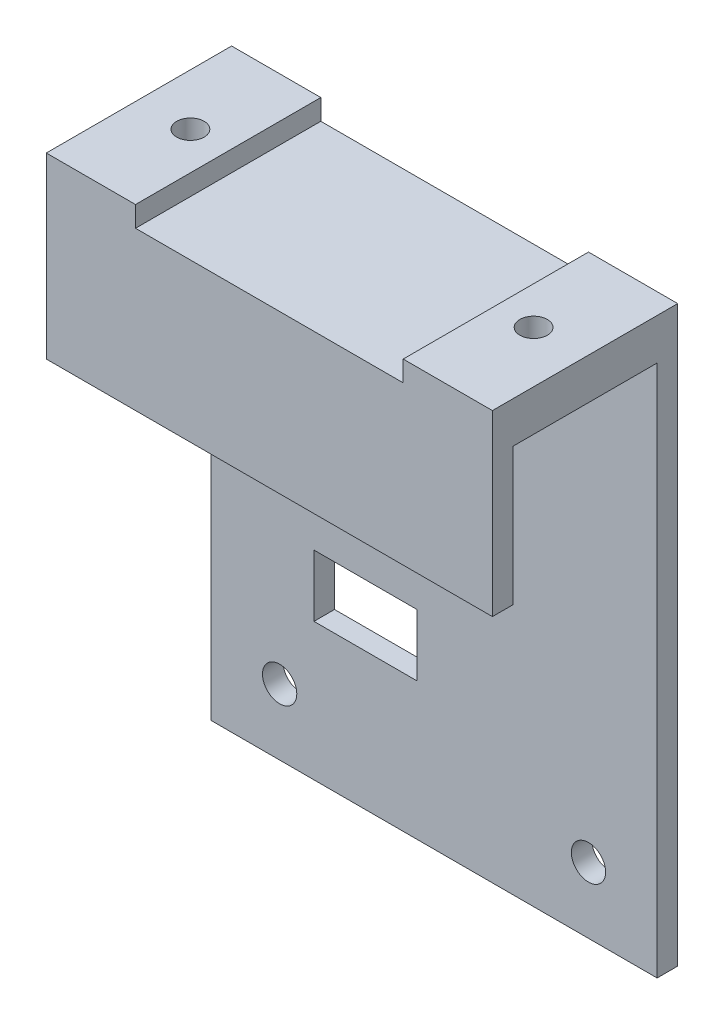
SolidWorks part; units mm, degrees
ref_plane "前视基准面" through (0, 0, 0) normal (0, 0, 1) x (1, 0, 0)
ref_plane "上视基准面" through (0, 0, 0) normal (0, 1, 0) x (1, 0, 0)
ref_plane "右视基准面" through (0, 0, 0) normal (1, 0, 0) x (0, 0, -1)
sketch "草图1" plane through (0, 0, 0) normal (0, 0, 1) x (1, 0, 0)
  line L1 (-32.5, -35) -> (32.5, -35)
  line L2 (-32.5, -35) -> (-32.5, 35)
  line L3 (-32.5, 35) -> (32.5, 35)
  line L4 (32.5, -35) -> (32.5, 35)
  line L5 (-32.5, -35) -> (32.5, 35) construction
  line L6 (-32.5, 35) -> (32.5, -35) construction
  point P0 (0, 0)
  dimension "D1" = 70
  dimension "D2" = 65
extrude "凸台-拉伸1" add sketch "草图1" along normal blind 3
sketch "草图2" plane through (0, 0, 3) normal (0, 0, 1) x (1, 0, 0)
  line L0 (32.5, -35) -> (32.5, 35) construction
  line L1 (-32.5, 35) -> (32.5, 35)
  line L2 (-32.5, 35) -> (-32.5, 29)
  line L3 (-32.5, 29) -> (32.5, 29)
  line L4 (32.5, 35) -> (32.5, 29)
  dimension "D1" = 6
extrude "凸台-拉伸2" add sketch "草图2" along normal blind 21
sketch "草图3" plane through (0, 35, 0) normal (0, 1, 0) x (1, 0, 0)
  line L1 (-32.5, -24) -> (32.5, -24)
  line L2 (-32.5, -24) -> (-32.5, -27)
  line L3 (-32.5, -27) -> (32.5, -27)
  line L4 (32.5, -24) -> (32.5, -27)
  dimension "D1" = 3
extrude "凸台-拉伸3" add sketch "草图3" against normal blind 26
sketch "草图4" plane through (0, 0, 27) normal (0, 0, 1) x (1, 0, 0)
  line L0 (-32.5, 35) -> (32.5, 35) construction
  line L1 (-19.5, 35) -> (19.5, 35)
  line L2 (-19.5, 35) -> (-19.5, 32)
  line L3 (-19.5, 32) -> (19.5, 32)
  line L4 (19.5, 35) -> (19.5, 32)
  line L5 (-32.5, 9) -> (-32.5, 35) construction
  line L6 (32.5, 9) -> (32.5, 35) construction
  dimension "D1" = 13
  dimension "D2" = 13
  dimension "D3" = 3
extrude "切除-拉伸1" cut sketch "草图4" against normal through all
sketch "草图5" plane through (0, 35, 0) normal (0, 1, 0) x (1, 0, 0)
  line L0 (0, 0) -> (25, 0)
  line L1 (32.5, 0) -> (19.5, 0) construction
  line L2 (0, 0) -> (-25, 0)
  line L3 (-19.5, 0) -> (-32.5, 0) construction
  line L4 (-25, 0) -> (-25, -13.5)
  line L7 (25, 0) -> (25, -13.5)
  circle A0 centre (-25, -13.5) radius 2
  circle A1 centre (25, -13.5) radius 2
  dimension "D5" = 4
  dimension "D6" = 4
  dimension "D1" = 25
  dimension "D2" = 25
  dimension "D3" = 13.5
  dimension "D4" = 13.5
extrude "切除-拉伸2" cut sketch "草图5" against normal through all contours A0 | A1
sketch "草图6" plane through (0, -35, 0) normal (0, -1, 0) x (1, 0, 0)
  line L4 (-32.5, 0) -> (32.5, 0)
  line L5 (32.5, 0) -> (32.5, 3)
  line L6 (32.5, 3) -> (-32.5, 3)
  line L7 (-32.5, 3) -> (-32.5, 0)
  line L8 (-32.5, 0) -> (32.5, 0)
  line L9 (32.5, 0) -> (32.5, 3)
  line L10 (32.5, 3) -> (-32.5, 3)
  line L11 (-32.5, 3) -> (-32.5, 0)
  dimension "D1" = 0
extrude "凸台-拉伸4" add sketch "草图6" along normal blind 13.6
sketch "草图7" plane through (0, 0, 3) normal (0, 0, 1) x (1, 0, 0)
  line L0 (32.5, -48.6) -> (-32.5, -48.6) construction
  line L1 (-32.5, 29) -> (-32.5, -48.6) construction
  line L2 (32.5, -48.6) -> (32.5, 29) construction
  circle A0 centre (-22.5, -39) radius 2.5
  circle A1 centre (22.5, -39) radius 2.5
  dimension "D1" = 5
  dimension "D2" = 5
  dimension "D3" = 9.6
  dimension "D4" = 9.6
  dimension "D5" = 10
  dimension "D6" = 10
extrude "切除-拉伸3" cut sketch "草图7" against normal through all contours A0 | A1
sketch "草图8" plane through (0, 0, 3) normal (0, 0, 1) x (1, 0, 0)
  line L0 (32.5, -48.6) -> (-32.5, -48.6) construction
  line L1 (-17.5, -19.6) -> (-2.5, -19.6)
  line L2 (-17.5, -19.6) -> (-17.5, -28.6)
  line L3 (-17.5, -28.6) -> (-2.5, -28.6)
  line L4 (-2.5, -19.6) -> (-2.5, -28.6)
  line L5 (-17.5, -19.6) -> (-2.5, -28.6) construction
  line L6 (-17.5, -28.6) -> (-2.5, -19.6) construction
  line L7 (-32.5, 29) -> (-32.5, -48.6) construction
  point P0 (-10, -24.1)
  dimension "D1" = 20
  dimension "D2" = 9
  dimension "D3" = 15
  dimension "D4" = 15
extrude "切除-拉伸4" cut sketch "草图8" against normal through all
